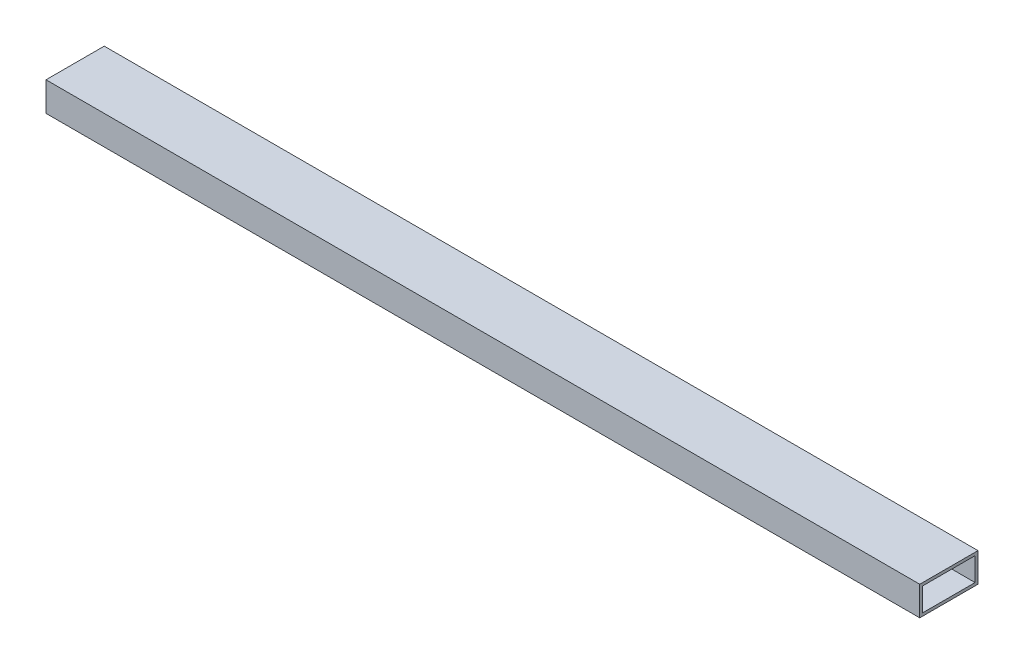
SolidWorks part; units mm, degrees
ref_plane "Front Plane" through (0, 0, 0) normal (0, 0, 1) x (1, 0, 0)
ref_plane "Top Plane" through (0, 0, 0) normal (0, 1, 0) x (1, 0, 0)
ref_plane "Right Plane" through (0, 0, 0) normal (1, 0, 0) x (0, 0, -1)
sketch "Sketch1" plane through (0, 0, 0) normal (1, 0, 0) x (0, 0, -1)
  line L0 (-9, -4) -> (9, -4)
  line L1 (-10, -5) -> (10, -5)
  line L2 (-10, -5) -> (-10, 5)
  line L3 (-10, 5) -> (10, 5)
  line L4 (10, -5) -> (10, 5)
  line L5 (-10, -5) -> (10, 5) construction
  line L6 (-10, 5) -> (10, -5) construction
  line L7 (9, -4) -> (9, 4)
  line L8 (-9, 4) -> (9, 4)
  line L9 (-9, -4) -> (-9, 4)
  point P0 (0, 0)
  dimension "D1" = 20
  dimension "D2" = 10
  dimension "D3" = 1
extrude "Boss-Extrude1" add sketch "Sketch1" along normal blind 300
